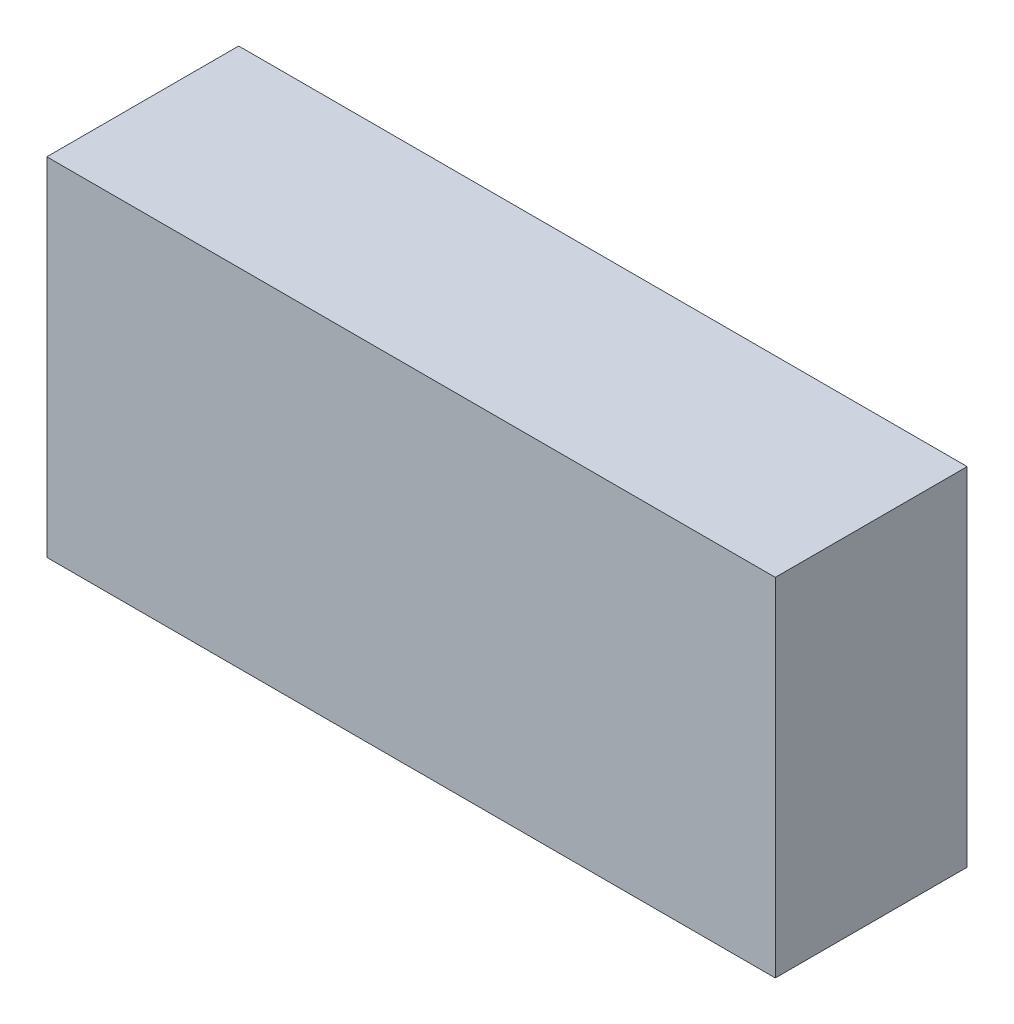
SolidWorks part; units mm, degrees
ref_plane "Front Plane" through (0, 0, 0) normal (0, 0, 1) x (1, 0, 0)
ref_plane "Top Plane" through (0, 0, 0) normal (0, 1, 0) x (1, 0, 0)
ref_plane "Right Plane" through (0, 0, 0) normal (1, 0, 0) x (0, 0, -1)
sketch "Sketch1" plane through (0, 0, 0) normal (0, 0, 1) x (1, 0, 0)
  line L0 (-1.8984, 0.9084) -> (1.8984, 0.9084)
  line L1 (1.8984, 0.9084) -> (1.8984, -0.9)
  line L2 (1.8984, -0.9) -> (-1.8984, -0.9)
  line L3 (-1.8984, -0.9) -> (-1.8984, 0.9084)
extrude "Component_Outline" add sketch "Sketch1" along normal blind 1 separate body
sketch3d "3DSketch1"
  line L0 (0, 0, 0) -> (1, 0, 0)
  line L1 (0, 0, 0) -> (0, 1, 0)
  line L2 (0, 0, 0) -> (0, 0, 1)
  point P0 (0, 0, 0)
